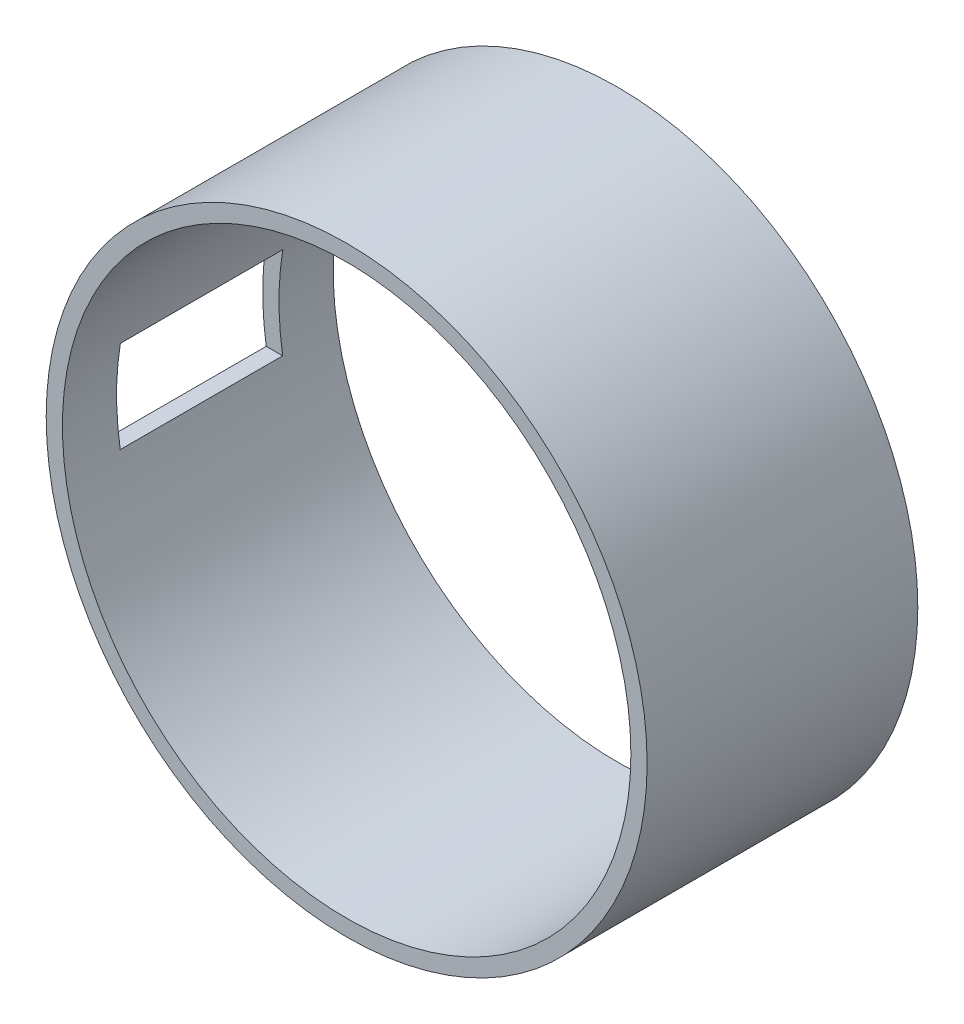
SolidWorks part; units mm, degrees
ref_plane "前视基准面" through (0, 0, 0) normal (0, 0, 1) x (1, 0, 0)
ref_plane "上视基准面" through (0, 0, 0) normal (0, 1, 0) x (1, 0, 0)
ref_plane "右视基准面" through (0, 0, 0) normal (1, 0, 0) x (0, 0, -1)
sketch "草图1" plane through (0, 0, 0) normal (0, 0, 1) x (1, 0, 0)
  circle A0 centre (0, 0) radius 10.5
  circle A1 centre (0, 0) radius 11.1
  dimension "D1" = 21
  dimension "D2" = 22.2
extrude "凸台-拉伸1" add sketch "草图1" along normal blind 10
sketch "草图2" plane through (0, 0, 10) normal (0, 0, 1) x (1, 0, 0)
  line L0 (-11.1, 0) -> (-10.5, 0) construction
  circle A0 centre (0, 0) radius 11.1 construction
  circle A1 centre (0, 0) radius 10.5 construction
ref_plane "基准面1" through (-11.1, 0, 0) normal (-1, 0, 0) x (0, 0, 1)
sketch "草图3" plane through (-11.1, 0, 0) normal (-1, 0, 0) x (0, 0, 1)
  line L0 (0, 0) -> (2, 0) construction
  line L1 (2, 0) -> (2, 1.7148) construction
  line L3 (2, 1.7148) -> (8, 1.7148)
  line L4 (2, 1.7148) -> (2, -1.6852)
  line L5 (2, -1.6852) -> (8, -1.6852)
  line L6 (8, 1.7148) -> (8, -1.6852)
  dimension "D1" = 6
  dimension "D2" = 3.4
extrude "切除-拉伸1" cut sketch "草图3" against normal blind 1.5
